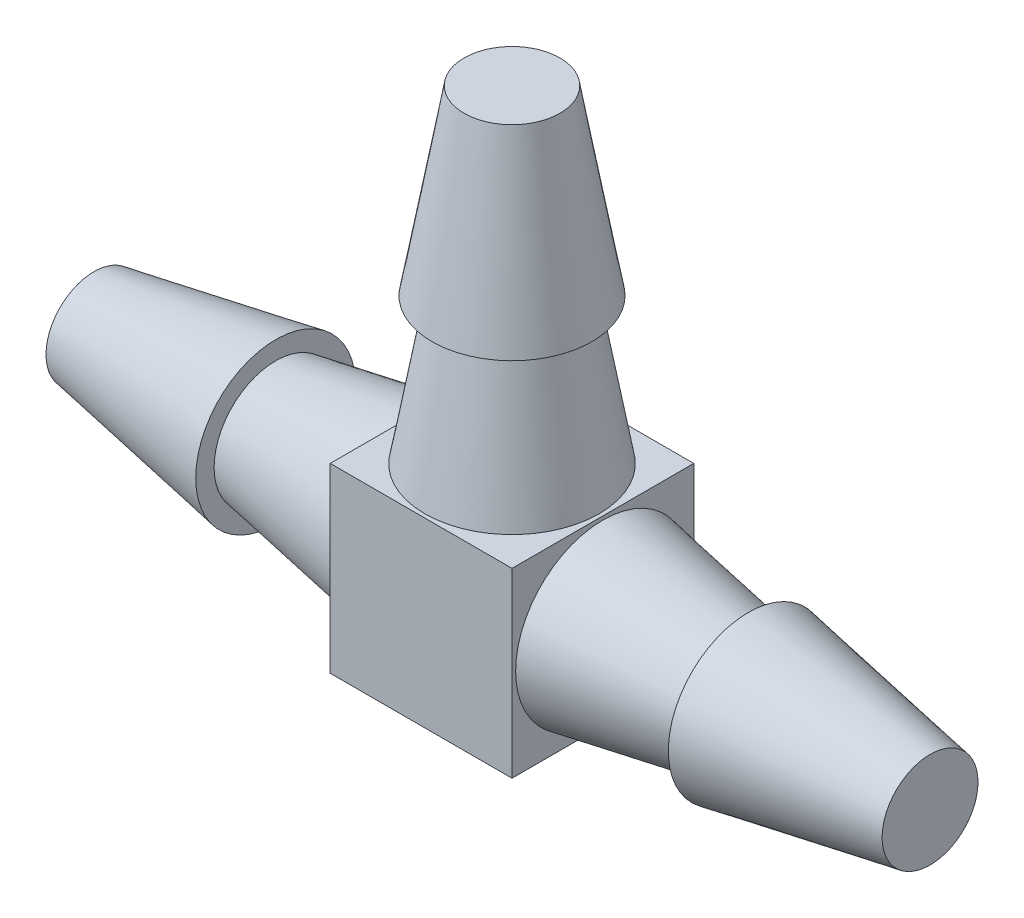
SolidWorks part; units mm, degrees
material "ABS"
ref_plane "Plan de face" through (0, 0, 0) normal (0, 0, 1) x (1, 0, 0)
ref_plane "Plan de dessus" through (0, 0, 0) normal (0, 1, 0) x (1, 0, 0)
ref_plane "Plan de droite" through (0, 0, 0) normal (1, 0, 0) x (0, 0, -1)
sketch "Esquisse1" plane through (0, 0, 0) normal (0, 0, 1) x (1, 0, 0)
  line L0 (-19.3294, -8.2685) -> (-19.3294, -13.2685)
  line L1 (-19.3294, -8.2685) -> (-14.3294, -8.2685)
  line L2 (-19.3294, -13.2685) -> (-14.3294, -13.2685)
  line L3 (-14.3294, -8.2685) -> (-14.3294, -13.2685)
  dimension "D1" = 5
  dimension "D2" = 5
extrude "Extrusion1" add sketch "Esquisse1" along normal blind 5
sketch "Esquisse2" plane through (-14.3294, 0, 0) normal (1, 0, 0) x (0, 0, -1)
  circle A0 centre (-2.5, -10.7685) radius 2.4
extrude "Extrusion2" add sketch "Esquisse2" along normal blind 4 draft 10
sketch "Esquisse3" plane through (0, -8.2685, 0) normal (0, 1, 0) x (-1, 0, 0)
  circle A0 centre (16.8294, 2.5) radius 2.4
extrude "Extrusion3" add sketch "Esquisse3" along normal blind 4 draft 10
sketch "Esquisse4" plane through (-19.3294, 0, 0) normal (-1, 0, 0) x (0, 0, 1)
  circle A0 centre (2.5, -10.7685) radius 2.4
extrude "Extrusion4" add sketch "Esquisse4" along normal blind 4 draft 10
sketch "Esquisse5" plane through (-23.3294, 0, 0) normal (-1, 0, 0) x (0, 0, 1)
  circle A0 centre (2.5, -10.7685) radius 2.2
extrude "Extrusion5" add sketch "Esquisse5" along normal blind 5 draft 10
sketch "Esquisse6" plane through (0, -4.2685, 0) normal (0, 1, 0) x (-1, 0, 0)
  circle A0 centre (16.8294, 2.5) radius 2.2
extrude "Extrusion6" add sketch "Esquisse6" along normal blind 5 draft 10
sketch "Esquisse7" plane through (-10.3294, 0, 0) normal (1, 0, 0) x (0, 0, -1)
  circle A0 centre (-2.5, -10.7685) radius 2.2
extrude "Extrusion7" add sketch "Esquisse7" along normal blind 5 draft 10
